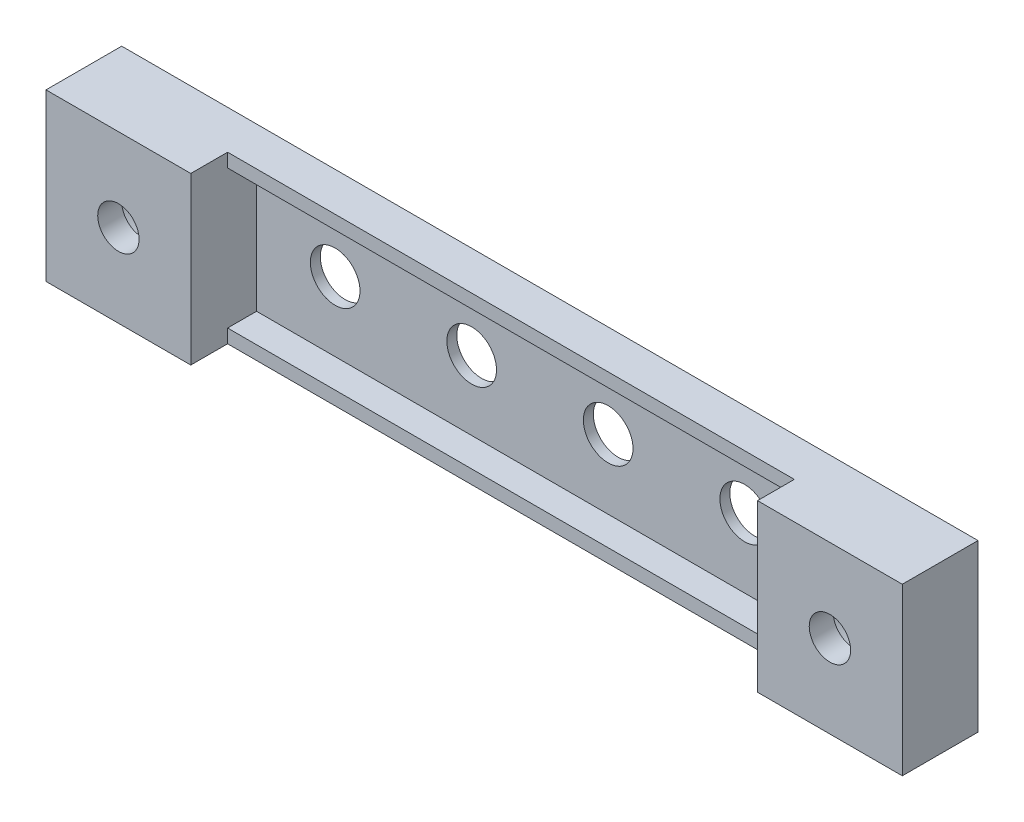
SolidWorks part; units mm, degrees
ref_plane "정면" through (0, 0, 0) normal (0, 0, 1) x (1, 0, 0)
ref_plane "윗면" through (0, 0, 0) normal (0, 1, 0) x (1, 0, 0)
ref_plane "우측면" through (0, 0, 0) normal (1, 0, 0) x (0, 0, -1)
sketch "스케치1" plane through (0, 0, 0) normal (0, 0, 1) x (1, 0, 0)
  line L1 (-16.7, -0.3307) -> (16.7, -0.3307)
  line L2 (-16.7, -0.3307) -> (-16.7, 0.3307)
  line L3 (-13.7, 0.3307) -> (13.7, 0.3307)
  line L4 (16.7, -0.3307) -> (16.7, 0.3307)
  line L5 (-16.7, -0.3307) -> (0, 0) construction
  line L6 (0, 0) -> (16.7, -0.3307) construction
  line L7 (-13.7, 7.0307) -> (13.7, 7.0307)
  line L8 (-16.7, 7.0307) -> (-16.7, 7.6922)
  line L9 (-16.7, 7.6922) -> (16.7, 7.6922)
  line L10 (16.7, 7.0307) -> (16.7, 7.6922)
  line L12 (-16.7, 7.0307) -> (-16.7, 0.3307)
  line L14 (-13.7, 7.0307) -> (-13.7, 0.3307)
  line L16 (16.7, 7.0307) -> (16.7, 0.3307)
  line L18 (13.7, 7.0307) -> (13.7, 0.3307)
  point P0 (0, 0)
  dimension "D1" = 6.7
  dimension "D2" = 3
  dimension "D3" = 3
extrude "보스-돌출1" add sketch "스케치1" along normal blind 1.4
sketch "스케치2" plane through (0, 0, 1.4) normal (0, 0, 1) x (1, 0, 0)
  line L0 (-16.7, -0.3307) -> (16.7, -0.3307) construction
  line L1 (-16.7, 7.6922) -> (-13.7, 7.6922)
  line L2 (-16.7, 7.6922) -> (-16.7, -0.3307)
  line L3 (-16.7, -0.3307) -> (-13.7, -0.3307)
  line L4 (-13.7, 7.6922) -> (-13.7, -0.3307)
  line L6 (16.7, 7.6922) -> (13.7, 7.6922)
  line L7 (16.7, 7.6922) -> (16.7, -0.3307)
  line L8 (16.7, -0.3307) -> (13.7, -0.3307)
  line L9 (13.7, 7.6922) -> (13.7, -0.3307)
extrude "보스-돌출2" add sketch "스케치2" along normal blind 1.78
sketch "스케치3" plane through (0, 0, 0) normal (0, 0, -1) x (-1, 0, 0)
  line L3 (16.7, 7.6922) -> (-16.7, 7.6922)
  line L4 (16.7, 7.6922) -> (16.7, -0.3307)
  line L6 (16.7, -0.3307) -> (-16.7, -0.3307)
  line L8 (-16.7, 7.6922) -> (-16.7, -0.3307)
extrude "보스-돌출6" add sketch "스케치3" along normal blind 0.58
sketch "스케치4" plane through (0, 0, -0.58) normal (0, 0, -1) x (-1, 0, 0)
  line L0 (-16.7, 3.6807) -> (-12.7, 3.6807) construction
  line L1 (-16.7, 7.6922) -> (-16.7, -0.3307) construction
  line L2 (-12.7, 3.6807) -> (-9.9, 3.6807) construction
  circle A0 centre (-9.9, 3.6807) radius 1.2
  circle A1 centre (-3.3, 3.6807) radius 1.2
  circle A2 centre (3.3, 3.6807) radius 1.2
  circle A3 centre (9.9, 3.6807) radius 1.2
  dimension "D1" = 4
extrude "컷-돌출1" cut sketch "스케치4" against normal blind 1
sketch "스케치6" plane through (0, 0, -0.58) normal (0, 0, -1) x (-1, 0, 0)
  line L1 (16.7, -0.3307) -> (-16.7, -0.3307)
  line L2 (16.7, -0.3307) -> (16.7, 7.6922)
  line L3 (16.7, 7.6922) -> (-16.7, 7.6922)
  line L4 (-16.7, -0.3307) -> (-16.7, 7.6922)
extrude "컷-돌출3" cut sketch "스케치6" against normal blind 0.1
sketch "스케치7" plane through (-16.7, 0, 0) normal (-1, 0, 0) x (0, 0, 1)
  line L1 (-0.48, -0.3307) -> (3.18, -0.3307)
  line L2 (-0.48, -0.3307) -> (-0.48, 7.6922)
  line L3 (-0.48, 7.6922) -> (3.18, 7.6922)
  line L4 (3.18, -0.3307) -> (3.18, 7.6922)
extrude "보스-돌출7" add sketch "스케치7" along normal blind 4
sketch "스케치8" plane through (0, 0, -0.48) normal (0, 0, -1) x (-1, 0, 0)
  line L0 (20.7, 7.6922) -> (20.7, -0.3307) construction
  circle A0 centre (17.2, 3.6807) radius 2.5
  point P2 (0, 0)
  dimension "D1" = 3.5
extrude "컷-돌출4" cut sketch "스케치8" against normal blind 2.5
sketch "스케치9" plane through (0, 0, 2.02) normal (0, 0, -1) x (-1, 0, 0)
  circle A0 centre (17.2, 3.6807) radius 1
extrude "컷-돌출5" cut sketch "스케치9" against normal blind 5 contours A0
sketch "스케치10" plane through (16.7, 0, 0) normal (1, 0, 0) x (0, 0, -1)
  line L1 (0.48, -0.3307) -> (-3.18, -0.3307)
  line L2 (0.48, -0.3307) -> (0.48, 7.6922)
  line L3 (0.48, 7.6922) -> (-3.18, 7.6922)
  line L4 (-3.18, -0.3307) -> (-3.18, 7.6922)
extrude "보스-돌출8" add sketch "스케치10" along normal blind 4
sketch "스케치11" plane through (0, 0, -0.48) normal (0, 0, -1) x (-1, 0, 0)
  line L0 (-20.7, -0.3307) -> (-20.7, 7.6922) construction
  circle A0 centre (-17.2, 3.6807) radius 2.5
  dimension "D1" = 3.5
extrude "컷-돌출6" cut sketch "스케치11" against normal blind 2.5 contours A0
sketch "스케치12" plane through (0, 0, 2.02) normal (0, 0, -1) x (-1, 0, 0)
  circle A0 centre (-17.2, 3.6807) radius 1
extrude "컷-돌출7" cut sketch "스케치12" against normal blind 2.5 contours A0
